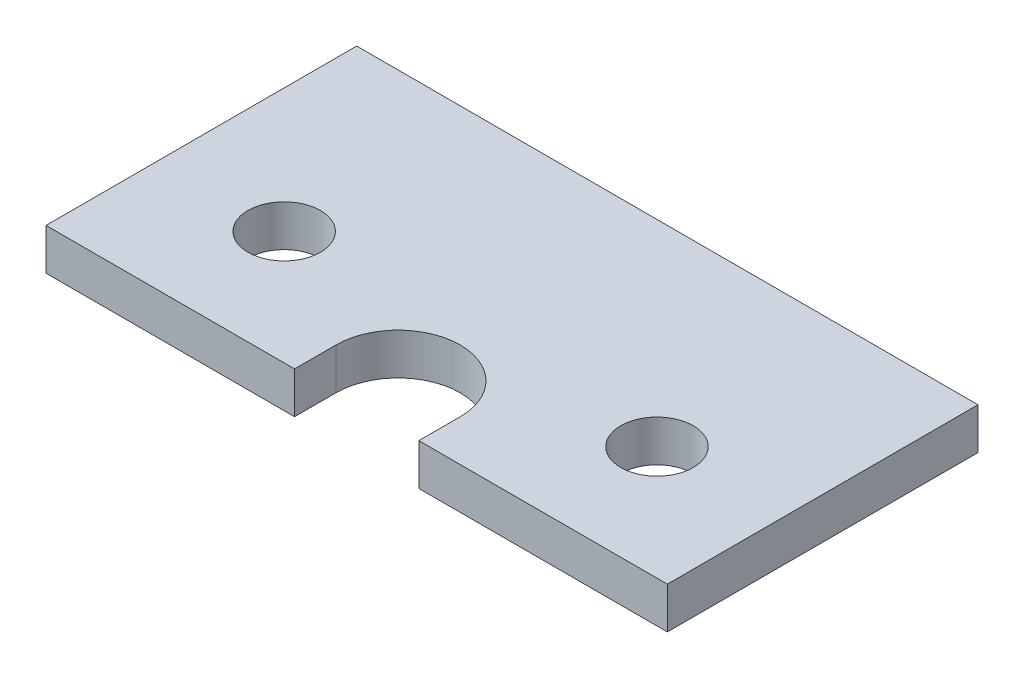
SolidWorks part; units mm, degrees
ref_plane "前基準面" through (0, 0, 0) normal (0, 0, 1) x (1, 0, 0)
ref_plane "上基準面" through (0, 0, 0) normal (0, 1, 0) x (1, 0, 0)
ref_plane "右基準面" through (0, 0, 0) normal (1, 0, 0) x (0, 0, -1)
sketch "草圖1" plane through (0, 0, 0) normal (0, 1, 0) x (1, 0, 0)
  line L0 (0, 5.5) -> (30, 5.5) construction
  line L1 (0, 0) -> (12, 0)
  line L2 (0, 0) -> (0, 15)
  line L3 (0, 15) -> (30, 15)
  line L4 (30, 0) -> (30, 15)
  line L5 (0, 2) -> (30, 2) construction
  line L6 (18, 2) -> (18, 0)
  line L7 (12, 2) -> (12, 0)
  line L8 (18, 0) -> (30, 0)
  circle A0 centre (24, 5.5) radius 1.75
  circle A1 centre (6, 5.5) radius 1.75
  arc A2 (18, 2) -> (12, 2) centre (15, 2) ccw
  dimension "D4" = 3.5
  dimension "D5" = 6
  dimension "D6" = 6
  dimension "D7" = 6
  dimension "D1" = 30
  dimension "D2" = 15
  dimension "D3" = 9.5
  dimension "D8" = 13
extrude "填料-伸長1" add sketch "草圖1" along normal blind 2
